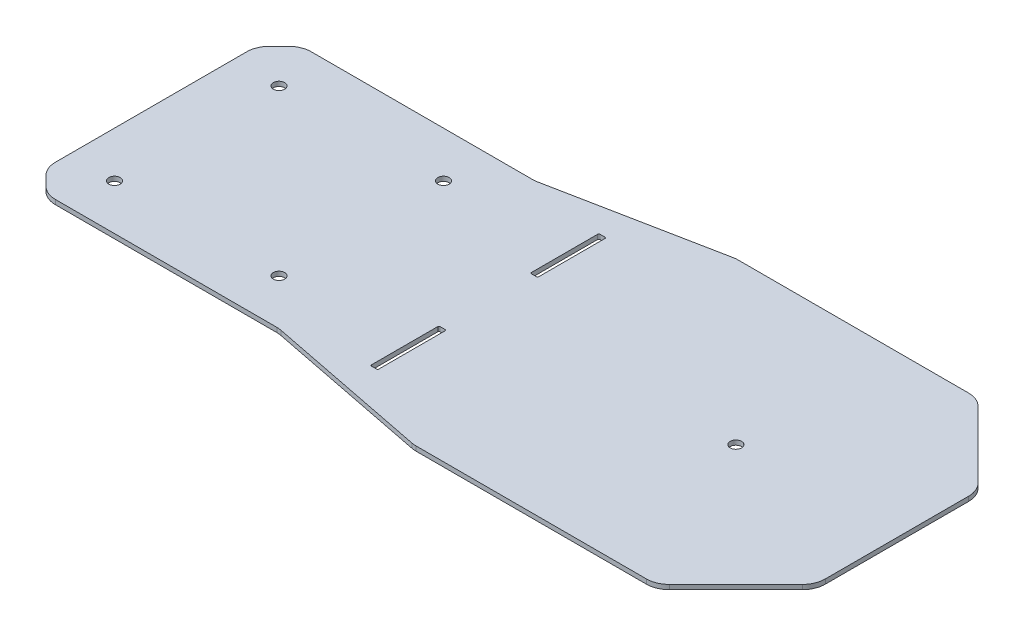
SolidWorks part; units mm, degrees
ref_plane "Front Plane" through (0, 0, 0) normal (0, 0, 1) x (1, 0, 0)
ref_plane "Top Plane" through (0, 0, 0) normal (0, 1, 0) x (1, 0, 0)
ref_plane "Right Plane" through (0, 0, 0) normal (1, 0, 0) x (0, 0, -1)
sketch "Sketch1" plane through (0, 0, 0) normal (0, 1, 0) x (1, 0, 0)
  line L0 (0, 0) -> (200, 0) construction
  line L1 (56, 56) -> (129.5, 70.5)
  line L2 (129.5, 70.5) -> (270.5, 70.5)
  line L3 (129.5, 70.5) -> (129.5, -70.5) construction
  line L4 (129.5, -70.5) -> (270.5, -70.5)
  line L5 (270.5, 70.5) -> (270.5, -70.5)
  line L6 (129.5, 70.5) -> (270.5, -70.5) construction
  line L7 (129.5, -70.5) -> (270.5, 70.5) construction
  line L8 (-56, 56) -> (56, 56)
  line L9 (-56, 56) -> (-56, -56)
  line L10 (-56, -56) -> (56, -56)
  line L11 (56, 56) -> (56, -56) construction
  line L12 (-56, 56) -> (56, -56) construction
  line L13 (-56, -56) -> (56, 56) construction
  line L14 (56, -56) -> (129.5, -70.5)
  dimension "D1" = 200
  dimension "D2" = 141
  dimension "D3" = 112
extrude "Boss-Extrude1" add sketch "Sketch1" along normal blind 2
chamfer "Chamfer1" distance 10 angle 45 2 edges at (-56, 1, -56) (-56, 1, 56)
chamfer "Chamfer2" distance 35 angle 45 2 edges at (270.5, 1, -70.5) (270.5, 1, 70.5)
fillet "Fillet1" radius 10 12 edges at (235.5, 1, 70.5) (270.5, 1, 35.5) (235.5, 1, -70.5) (270.5, 1, -35.5) (129.5, 1, 70.5) (56, 1, 56) (-46, 1, 56) (-56, 1, 46) (-56, 1, -46) (-46, 1, -56) (56, 1, -56) (129.5, 1, -70.5)
hole_wizard "Ø5.0mm Dowel Hole1" positions "Sketch3" profile "Sketch4" hole size "Ø5.0" standard "ANSI Metric" end condition up to next
sketch "Sketch3" plane through (0, 0, 0) normal (0, -1, 0) x (-1, 0, 0)
  line L1 (-55.023, 0) -> (56, 0) construction
  line L2 (56, 41.8579) -> (56, -41.8579) construction
  point P0 (36, -36)
  point P2 (-36, -36)
  point P342 (0, 0)
  point P343 (0, 0)
  point P344 (0, 0)
  point P346 (36, 36)
  point P347 (-36, 36)
  dimension "D1" = 72
  dimension "D2" = 36
  dimension "D3" = 36
sketch "Sketch4" plane through (-36, 0, 36) normal (1, 0, 0) x (0, 0, -1)
  line L0 (0, 0) -> (0, 2)
  line L1 (0, 2) -> (2.5, 2)
  line L2 (2.5, 2) -> (2.5, 0)
  line L5 (2.5, 0) -> (0, 0)
  line L11 (0, -6.35) -> (0, 107.95) construction
  dimension "Thru Hole Dia." = 5
  dimension "Thru Hole Depth" = 2
sketch "Sketch5" plane through (0, 2, 0) normal (0, 1, 0) x (1, 0, 0)
  circle A0 centre (200, 0) radius 2.5
  dimension "D1" = 200
  dimension "D2" = 5
extrude "Cut-Extrude2" cut sketch "Sketch5" against normal through all
sketch "Sketch6" plane through (0, 2, 0) normal (0, 1, 0) x (1, 0, 0)
  line L0 (-56, 0) -> (270.5, 0) construction
  line L1 (-56, 41.8579) -> (-56, -41.8579) construction
  line L2 (270.5, -31.3579) -> (270.5, 31.3579) construction
  line L3 (93.2, 20.5) -> (93.2, 49.5)
  line L4 (90.5, -20) -> (92.7, -20)
  line L5 (90, -20.5) -> (90, -49.5)
  line L6 (90.5, -50) -> (92.7, -50)
  line L7 (93.2, -20.5) -> (93.2, -49.5)
  line L8 (90.5, 50) -> (92.7, 50)
  line L9 (90, 20.5) -> (90, 49.5)
  line L10 (90.5, 20) -> (92.7, 20)
  arc A0 (90.5, -50) -> (90, -49.5) centre (90.5, -49.5) cw
  arc A1 (92.7, -50) -> (93.2, -49.5) centre (92.7, -49.5) ccw
  arc A2 (90, -20.5) -> (90.5, -20) centre (90.5, -20.5) cw
  arc A3 (93.2, -20.5) -> (92.7, -20) centre (92.7, -20.5) ccw
  arc A4 (93.2, 20.5) -> (92.7, 20) centre (92.7, 20.5) cw
  arc A5 (90, 20.5) -> (90.5, 20) centre (90.5, 20.5) ccw
  arc A6 (92.7, 50) -> (93.2, 49.5) centre (92.7, 49.5) cw
  arc A7 (90.5, 50) -> (90, 49.5) centre (90.5, 49.5) ccw
  point P13 (90, -50)
  point P16 (93.2, -50)
  point P19 (90, -20)
  point P34 (90, 20)
  point P35 (93.2, 50)
  point P36 (90, 50)
  dimension "D5" = 0.5
  dimension "D1" = 30
  dimension "D2" = 3.2
  dimension "D3" = 90
  dimension "D4" = 20
extrude "Cut-Extrude3" cut sketch "Sketch6" against normal through all
equation "\"Elevator Diameter\"= 135mm"
equation "\"Plate Thickness\"= 2mm"
equation "\"Pivot to Pivot Distance\"= 200mm"
equation "\"D1@Sketch1\"=\"Pivot to Pivot Distance\""
equation "\"Extra Spacing\"= 3mm"
equation "\"D2@Sketch1\"=\"Elevator Diameter\"+\"Extra Spacing\"*2"
equation "\"Servo Size\"= 40mm"
equation "\"D1@Boss-Extrude1\"=\"Plate Thickness\""
equation "\"D1@Sketch5\"=\"Pivot to Pivot Distance\""
